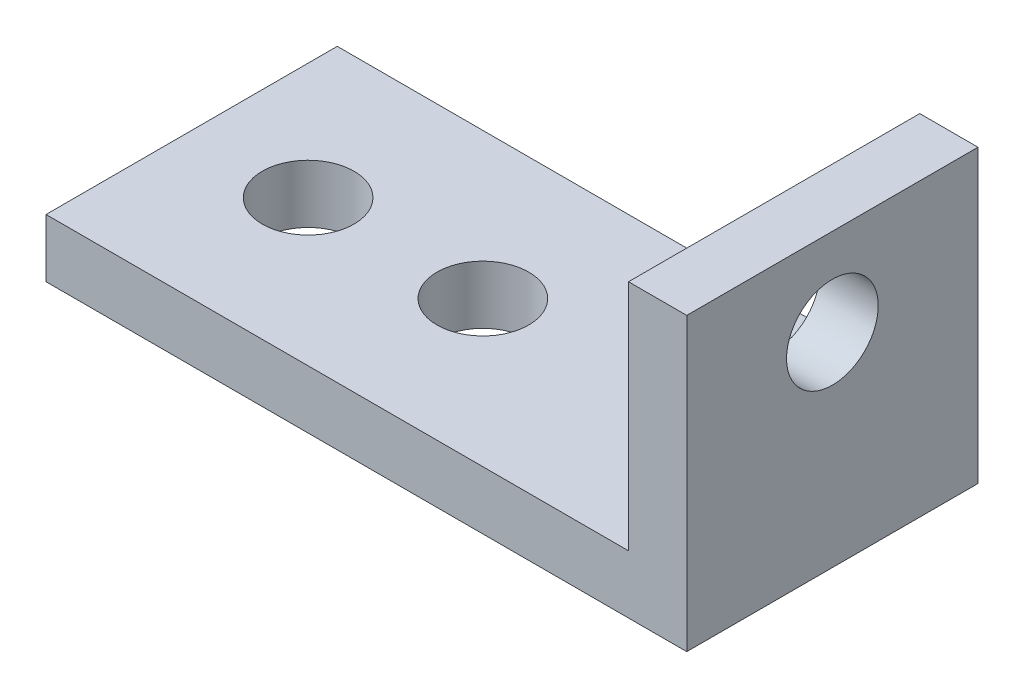
SolidWorks part; units mm, degrees
material "6061-T6 (SS)"
ref_plane "Front Plane" through (0, 0, 0) normal (0, 0, 1) x (1, 0, 0)
ref_plane "Top Plane" through (0, 0, 0) normal (0, 1, 0) x (1, 0, 0)
ref_plane "Right Plane" through (0, 0, 0) normal (1, 0, 0) x (0, 0, -1)
sketch "Sketch1" plane through (0, 0, 0) normal (0, 0, 1) x (1, 0, 0)
  line L0 (0, 0) -> (0, 2.54)
  line L1 (0, 2.54) -> (25.4, 2.54)
  line L2 (25.4, 2.54) -> (25.4, 12.7)
  line L3 (25.4, 12.7) -> (27.94, 12.7)
  line L4 (27.94, 12.7) -> (27.94, 0)
  line L5 (27.94, 0) -> (0, 0)
  dimension "D1" = 12.7
  dimension "D2" = 2.54
  dimension "D3" = 25.4
  dimension "D4" = 2.54
extrude "Boss-Extrude1" add sketch "Sketch1" along normal blind 12.7
sketch "Sketch2" plane through (25.4, 0, 0) normal (-1, 0, 0) x (0, 0, 1)
  line L0 (6.35, 12.7) -> (6.35, 2.54) construction
  line L3 (12.7, 12.7) -> (0, 12.7) construction
  line L4 (12.7, 2.54) -> (0, 2.54) construction
  circle A3 centre (6.35, 8.89) radius 2
  dimension "D1" = 4
  dimension "D2" = 3.81
sketch "Sketch3" plane through (0, 2.54, 0) normal (0, 1, 0) x (1, 0, 0)
  line L0 (0, -6.35) -> (25.4, -6.35) construction
  line L1 (0, -12.7) -> (0, 0) construction
  line L3 (25.4, -12.7) -> (25.4, 0) construction
  circle A0 centre (5.08, -6.35) radius 2
  circle A2 centre (12.7, -6.35) radius 2
  dimension "D3" = 4
  dimension "D4" = 7.62
  dimension "D2" = 5.08
extrude "Cut-Extrude1" cut sketch "Sketch3" against normal through all
extrude "Cut-Extrude2" cut sketch "Sketch2" against normal through all
sketch "Sketch4" plane through (25.4, 0, 0) normal (-1, 0, 0) x (0, 0, 1)
  circle A0 centre (6.35, 8.89) radius 3.5
  circle A1 centre (6.35, 8.89) radius 2 construction
  point P2 (12.2004, 5.715)
  dimension "D1" = 7
